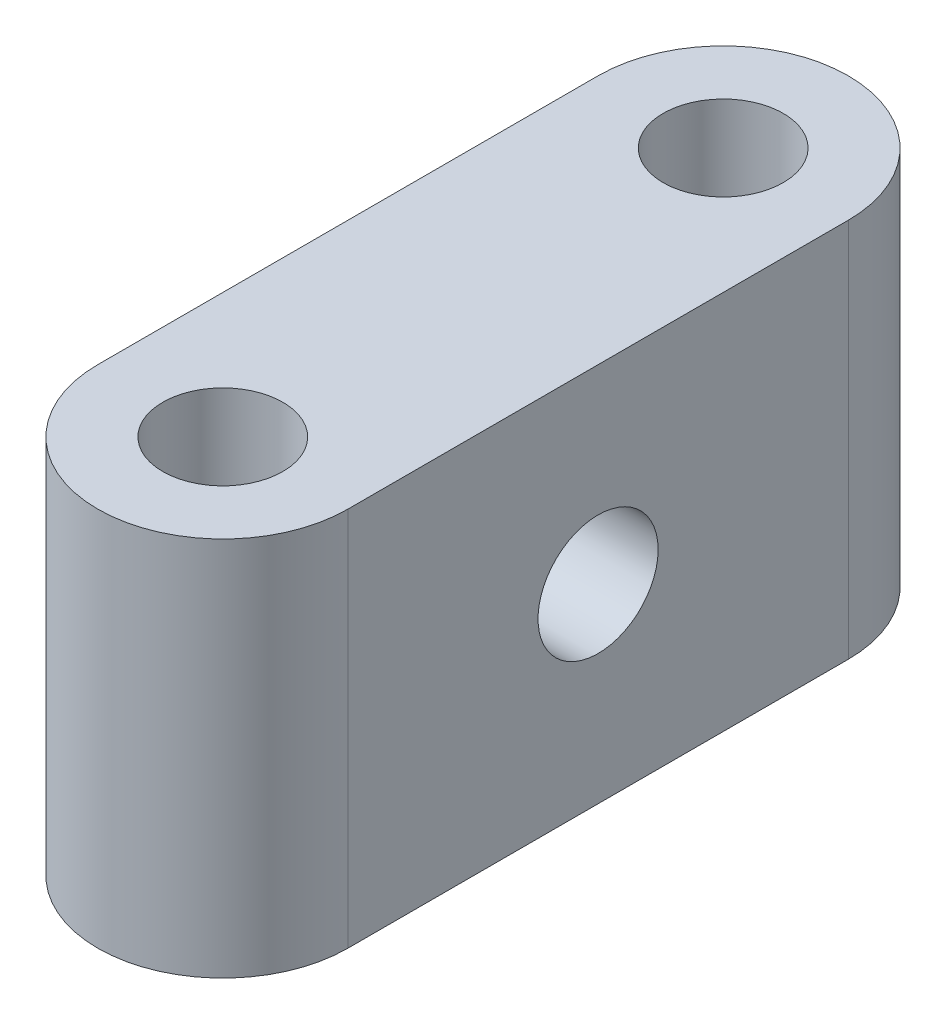
SolidWorks part; units mm, degrees
ref_plane "Front Plane" through (0, 0, 0) normal (0, 0, 1) x (1, 0, 0)
ref_plane "Top Plane" through (0, 0, 0) normal (0, 1, 0) x (1, 0, 0)
ref_plane "Right Plane" through (0, 0, 0) normal (1, 0, 0) x (0, 0, -1)
sketch "Sketch1" plane through (0, 0, 0) normal (0, 1, 0) x (1, 0, 0)
  line L0 (0, 0) -> (0, 50) construction
  line L1 (-12.5, 0) -> (-12.5, 50)
  line L2 (12.5, 0) -> (12.5, 50)
  arc A0 (-12.5, 0) -> (12.5, 0) centre (0, 0) ccw
  arc A1 (12.5, 50) -> (-12.5, 50) centre (0, 50) ccw
  circle A2 centre (0, 50) radius 6
  circle A3 centre (0, 0) radius 6
  point P3 (0, 25)
  dimension "D2" = 12.5
  dimension "D3" = 12
  dimension "D4" = 12
  dimension "D1" = 50
extrude "Boss-Extrude1" add sketch "Sketch1" along normal mid plane 38
sketch "Sketch2" plane through (12.5, 0, 0) normal (1, 0, 0) x (0, 0, -1)
  line L3 (0, 19) -> (50, 19) construction
  circle A0 centre (25, 0) radius 6
  dimension "D1" = 12
  dimension "D2" = 25
  dimension "D3" = 19
extrude "Cut-Extrude1" cut sketch "Sketch2" against normal blind 12.5
